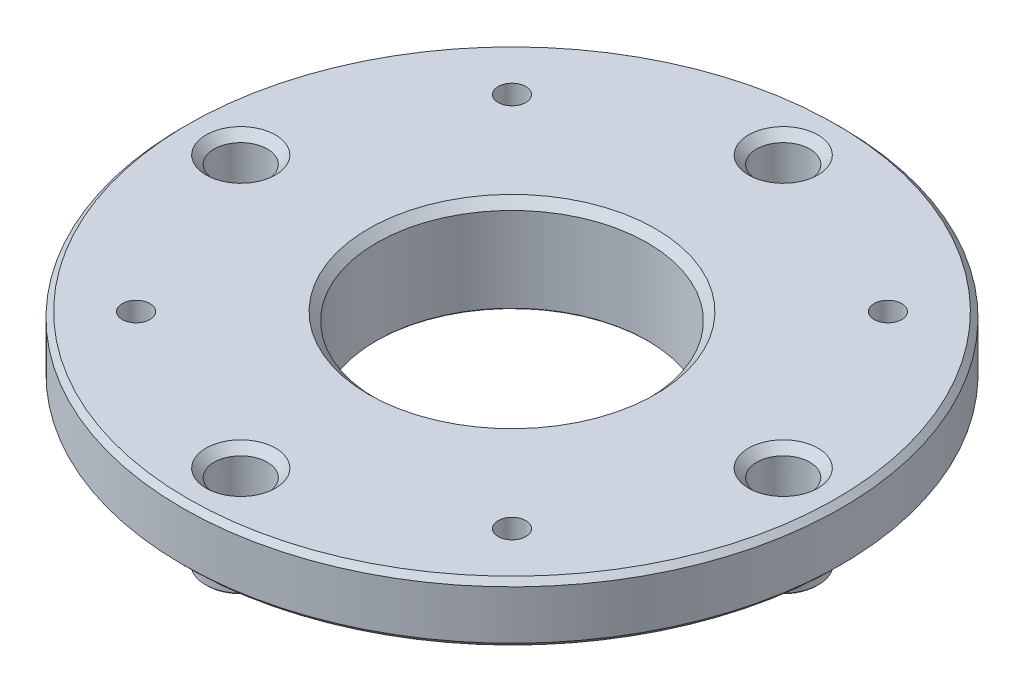
SolidWorks part; units mm, degrees
ref_plane "Front Plane" through (0, 0, 0) normal (0, 0, 1) x (1, 0, 0)
ref_plane "Top Plane" through (0, 0, 0) normal (0, 1, 0) x (1, 0, 0)
ref_plane "Right Plane" through (0, 0, 0) normal (1, 0, 0) x (0, 0, -1)
sketch "Sketch1" plane through (0, 0, 0) normal (0, 0, 1) x (1, 0, 0)
  line L0 (60.75, 11) -> (0, 11)
  line L1 (0, 11) -> (0, 0)
  line L2 (0, 0) -> (60.75, 0)
  line L3 (60.75, 0) -> (60.75, 11)
  line L4 (0, 11) -> (0, 0) construction
revolve "Revolve1" add sketch "Sketch1" angle 360 about L4
sketch "Sketch2" plane through (0, 0, 0) normal (0, -1, 0) x (1, 0, 0)
  circle A0 centre (0, 0) radius 28.485
extrude "Boss-Extrude1" add sketch "Sketch2" along normal blind 6.35
ref_plane "Plane1" through (0, 0, 0) normal (0, 0, -1) x (-1, 0, 0)
sketch "Sketch3" plane through (0, 0, 0) normal (0, 0, -1) x (-1, 0, 0)
  line L0 (43.525, -4.65) -> (50, -4.65)
  line L1 (50, -4.65) -> (50, 0)
  line L2 (50, 0) -> (43.525, 0)
  line L3 (43.525, 0) -> (43.525, -4.65)
  line L4 (50, -4.65) -> (50, 0) construction
revolve "Revolve2" add sketch "Sketch3" angle 360 about L4
ref_plane "Plane2" through (0, 0, -50) normal (0, 0, -1) x (-1, 0, 0)
sketch "Sketch4" plane through (0, 0, -50) normal (0, 0, -1) x (-1, 0, 0)
  line L0 (-6.475, -4.65) -> (0, -4.65)
  line L1 (0, -4.65) -> (0, 0)
  line L2 (0, 0) -> (-6.475, 0)
  line L3 (-6.475, 0) -> (-6.475, -4.65)
  line L4 (0, -4.65) -> (0, 0) construction
revolve "Revolve3" add sketch "Sketch4" angle 360 about L4
sketch "Sketch5" plane through (0, 0, 0) normal (0, 0, -1) x (-1, 0, 0)
  line L0 (-56.475, -4.65) -> (-50, -4.65)
  line L1 (-50, -4.65) -> (-50, 0)
  line L2 (-50, 0) -> (-56.475, 0)
  line L3 (-56.475, 0) -> (-56.475, -4.65)
  line L4 (-50, -4.65) -> (-50, 0) construction
revolve "Revolve4" add sketch "Sketch5" angle 360 about L4
ref_plane "Plane3" through (0, 0, 50) normal (0, 0, -1) x (-1, 0, 0)
sketch "Sketch6" plane through (0, 0, 50) normal (0, 0, -1) x (-1, 0, 0)
  line L0 (-6.475, -4.65) -> (0, -4.65)
  line L1 (0, -4.65) -> (0, 0)
  line L2 (0, 0) -> (-6.475, 0)
  line L3 (-6.475, 0) -> (-6.475, -4.65)
  line L4 (0, -4.65) -> (0, 0) construction
revolve "Revolve5" add sketch "Sketch6" angle 360 about L4
hole_wizard "Hole1" positions "Sketch8" profile "Sketch7" legacy
sketch "Sketch8" plane through (0, 11, 0) normal (0, 1, 0) x (1, 0, 0)
  point P0 (-34.6482, -34.6482)
  point P1 (34.6482, -34.6482)
  point P2 (34.6482, 34.6482)
  point P3 (-34.6482, 34.6482)
sketch "Sketch7" plane through (-34.6482, 11, 34.6482) normal (1, 0, 0) x (0, 0, 1)
  line L0 (0, 0) -> (0, 17.35)
  line L1 (0, 17.35) -> (2.5527, 17.35)
  line L2 (2.5527, 17.35) -> (2.5527, 0)
  line L3 (2.5527, 0) -> (0, 0)
  line L4 (0, 110) -> (0, -10) construction
  dimension "Diameter" = 5.1054
  dimension "Depth" = 17.35
hole_wizard "M8 Clearance Hole1" positions "Sketch10" profile "Sketch9" hole size "M8" standard "ANSI Metric"
sketch "Sketch10" plane through (0, 11, 0) normal (0, 1, 0) x (1, 0, 0)
  point P0 (50, 0)
  point P1 (0, -50)
  point P2 (-50, 0)
sketch "Sketch9" plane through (50, 11, 0) normal (1, 0, 0) x (0, 0, 1)
  line L0 (0, 0) -> (0, 17.35)
  line L1 (0, 17.35) -> (4.9022, 17.35)
  line L2 (4.9022, 17.35) -> (4.9022, 0)
  line L5 (4.9022, 0) -> (0, 0)
  line L11 (0, -6.35) -> (0, 107.95) construction
  dimension "Thru Hole Dia." = 9.8044
  dimension "Thru Hole Depth" = 17.35
hole_wizard "M45 Clearance Hole1" positions "Sketch12" profile "Sketch11" hole size "M45" standard "ANSI Metric"
sketch "Sketch12" plane through (0, 11, 0) normal (0, 1, 0) x (1, 0, 0)
  point P0 (0, 0)
sketch "Sketch11" plane through (0, 11, 0) normal (1, 0, 0) x (0, 0, 1)
  line L0 (0, 0) -> (0, 17.35)
  line L1 (0, 17.35) -> (24.9555, 17.35)
  line L2 (24.9555, 17.35) -> (24.9555, 0)
  line L5 (24.9555, 0) -> (0, 0)
  line L11 (0, -6.35) -> (0, 107.95) construction
  dimension "Thru Hole Dia." = 49.911
  dimension "Thru Hole Depth" = 17.35
hole_wizard "M8 Clearance Hole2" positions "Sketch14" profile "Sketch13" hole size "M8" standard "ANSI Metric"
sketch "Sketch14" plane through (0, -4.65, 0) normal (0, -1, 0) x (-1, 0, 0)
  point P0 (0, 50)
sketch "Sketch13" plane through (0, -4.65, -50) normal (1, 0, 0) x (0, 0, -1)
  line L0 (0, 0) -> (0, 15.65)
  line L1 (0, 15.65) -> (4.9022, 15.65)
  line L2 (4.9022, 15.65) -> (4.9022, 0)
  line L5 (4.9022, 0) -> (0, 0)
  line L11 (0, -6.35) -> (0, 107.95) construction
  dimension "Thru Hole Dia." = 9.8044
  dimension "Thru Hole Depth" = 15.65
chamfer "Chamfer1" distance 0.25 angle 45 9 edges at (0, -6.35, 24.9555) (0, -4.65, 45.0978) (-50, -4.65, -4.9022) (50, -4.65, -4.9022) (-50, -4.65, 6.475) (0, -4.65, 56.475) (50, -4.65, 6.475) (0, -4.65, -54.9022) (0, -4.65, -43.525)
chamfer "Chamfer2" distance 1 angle 45 3 edges at (0, 11, -60.75) (0, 0, -60.75) (0, -6.35, -28.485)
chamfer "Chamfer3" distance 1.5 angle 45 5 edges at (0, 11, -54.9022) (50, 11, 4.9022) (0, 11, 24.9555) (0, 11, 54.9022) (-50, 11, 4.9022)
